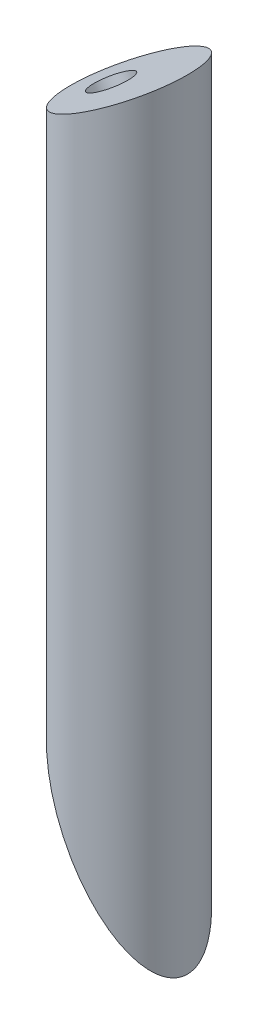
SolidWorks part; units mm, degrees
ref_plane "Front Plane" through (0, 0, 0) normal (0, 0, 1) x (1, 0, 0)
ref_plane "Top Plane" through (0, 0, 0) normal (0, 1, 0) x (1, 0, 0)
ref_plane "Right Plane" through (0, 0, 0) normal (1, 0, 0) x (0, 0, -1)
sketch "Sketch2" plane through (0, 0, 0) normal (0, 1, 0) x (1, 0, 0)
  circle A0 centre (0, 0) radius 7.5
  dimension "D1" = 15
extrude "Boss-Extrude1" add sketch "Sketch2" along normal blind 100
sketch "Sketch3" plane through (0, 0, 0) normal (0, 0, 1) x (1, 0, 0)
  line L0 (7.5, 0) -> (7.5, -12.7682)
  line L1 (7.5, -12.7682) -> (-21.2216, -12.7682)
  line L2 (-21.2216, -12.7682) -> (-21.2216, 49.7473)
  line L3 (-21.2216, 49.7473) -> (7.5, 0)
  line L4 (7.5, 100) -> (-17.2439, 85.7141)
  line L5 (-17.2439, 85.7141) -> (-17.2439, 115.1807)
  line L6 (-17.2439, 115.1807) -> (7.5, 115.1807)
  line L7 (7.5, 115.1807) -> (7.5, 100)
  line L8 (7.5, 100) -> (-7.5, 100) construction
  line L9 (-7.5, 0) -> (7.5, 0) construction
  line L10 (7.5, 0) -> (7.5, 100) construction
  line L11 (-7.5, 100) -> (-7.5, 0) construction
  point P14 (-21.2216, -12.7682)
  dimension "D1" = 30
  dimension "D2" = 60
  dimension "D3" = 15.1807
  dimension "D4" = 24.7439
  dimension "D5" = 13.7216
  dimension "D6" = 12.7682
extrude "Cut-Extrude1" cut sketch "Sketch3" against normal mid plane 100
sketch "Sketch4" plane through (-41.4263, 71.7524, 0) normal (-0.5, 0.866, 0) x (0.866, 0.5, 0)
  circle A0 centre (45.1747, 0) radius 2.5
  ellipse E0 centre (47.8349, 0) end of major axis (39.1747, 0) minor radius 7.5 construction
  ellipse E1 centre (47.8349, 0) end of major axis (39.1747, 0) minor radius 7.5
  point P2 (39.1747, 0)
  point P3 (42.6747, 0)
  point P15 (0, 0)
  point P16 (0, 0)
  point P17 (45.1747, 0)
  point P18 (0, 0)
  dimension "D1" = 5
  dimension "D2" = 6
  dimension "D3" = 3.5
extrude "Cut-Extrude2" cut sketch "Sketch4" against normal blind 10 contours A0
sketch "Sketch5" plane through (5.625, 3.2476, 0) normal (-0.866, -0.5, 0) x (0, 0, 1)
  circle A0 centre (0, 18.25) radius 2.5
  ellipse E0 centre (0, 11.25) end of major axis (0, -3.75) minor radius 7.5 construction
  point P2 (0, 26.25)
  point P3 (0, 0)
  point P11 (0, 18.25)
  dimension "D1" = 5
  dimension "D2" = 8
  dimension "D3" = 18.25
extrude "Cut-Extrude3" cut sketch "Sketch5" against normal blind 7
